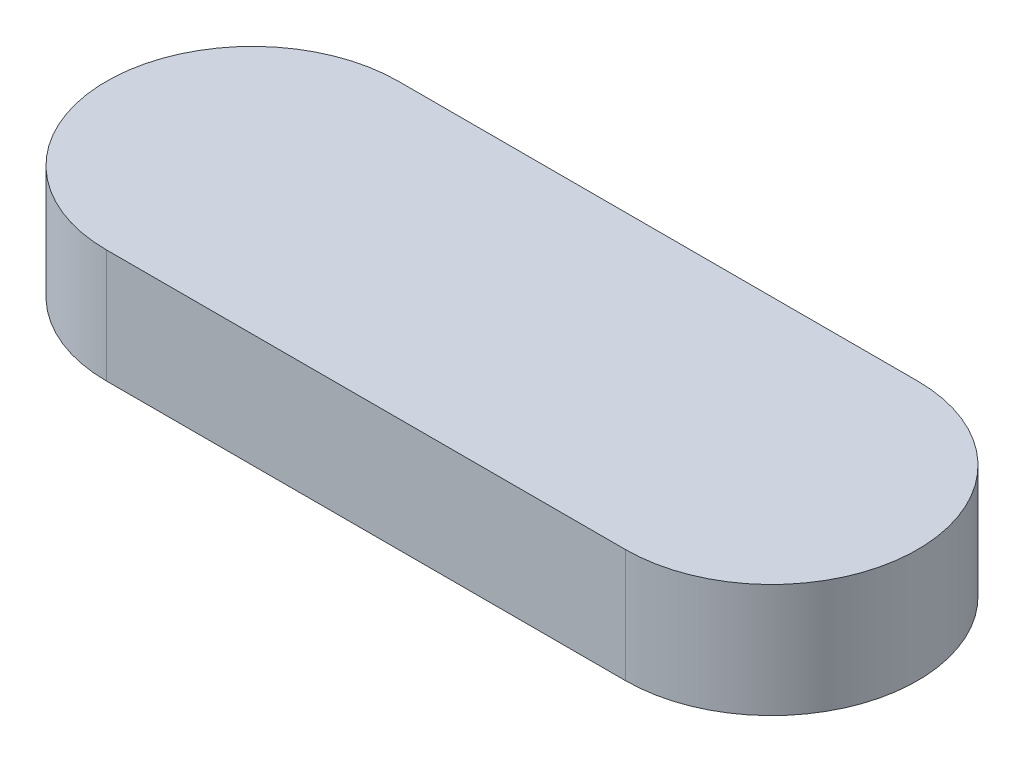
SolidWorks part; units mm, degrees
ref_plane "Front Plane" through (0, 0, 0) normal (0, 0, 1) x (1, 0, 0)
ref_plane "Top Plane" through (0, 0, 0) normal (0, 1, 0) x (1, 0, 0)
ref_plane "Right Plane" through (0, 0, 0) normal (1, 0, 0) x (0, 0, -1)
sketch "Sketch1" plane through (0, 0, 0) normal (0, 1, 0) x (1, 0, 0)
  line L0 (0, 0) -> (12689.6297, 0) construction
  line L1 (-16, 0) -> (16, 0) construction
  line L2 (-16, 9) -> (16, 9)
  line L3 (-16, -9) -> (16, -9)
  arc A0 (-16, 9) -> (-16, -9) centre (-16, 0) ccw
  arc A1 (16, -9) -> (16, 9) centre (16, 0) ccw
  point P5 (0, 0)
  point P10 (0, 0)
  point P11 (0, 0)
  point P12 (0, 0)
  dimension "D2" = 9
  dimension "D1" = 32
extrude "Boss-Extrude1" add sketch "Sketch1" along normal blind 7
